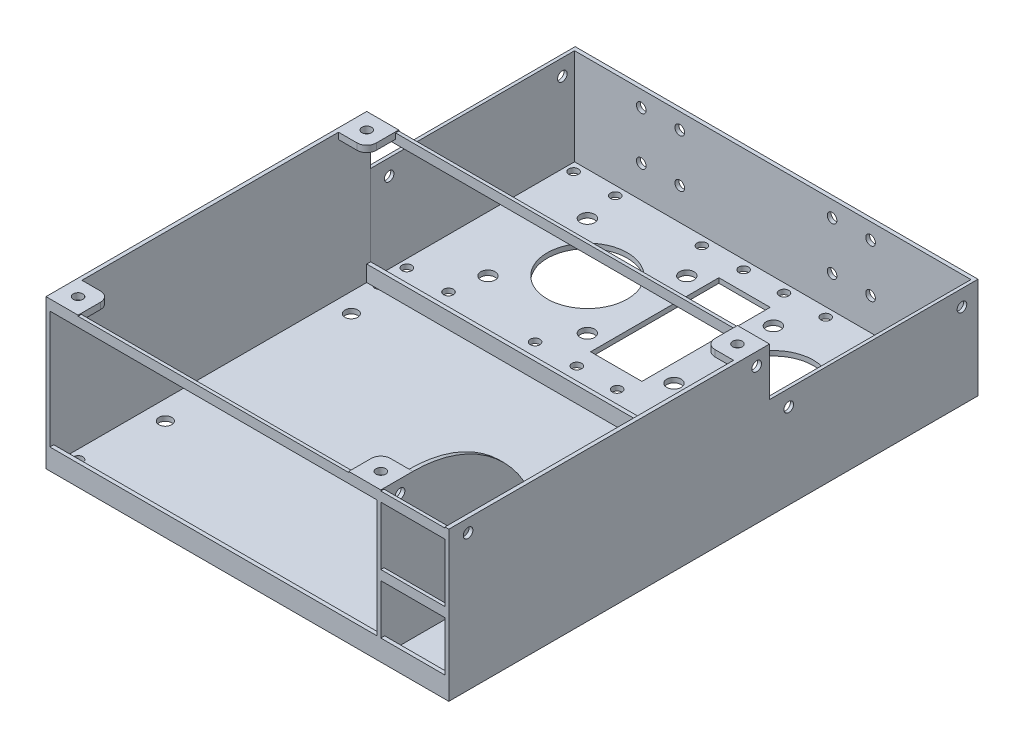
SolidWorks part; units mm, degrees
ref_plane "前视基准面" through (0, 0, 0) normal (0, 0, 1) x (1, 0, 0)
ref_plane "上视基准面" through (0, 0, 0) normal (0, 1, 0) x (1, 0, 0)
ref_plane "右视基准面" through (0, 0, 0) normal (1, 0, 0) x (0, 0, -1)
sketch "草图1" plane through (0, 0, 0) normal (0, 1, 0) x (1, 0, 0)
  line L0 (50.2, 20) -> (50.2, 102.702) construction
  line L1 (0, 0) -> (125.6, 0)
  line L2 (0, 0) -> (0, 165)
  line L3 (0, 165) -> (125.6, 165)
  line L4 (125.6, 0) -> (125.6, 165)
  line L5 (93.2, 0) -> (93.2, 165) construction
  line L6 (62.8, 0) -> (62.8, 178.9026) construction
  line L7 (109.4, 78) -> (119.4, 78)
  line L8 (109.4, 78) -> (109.4, 55)
  line L9 (109.4, 55) -> (119.4, 55)
  line L10 (119.4, 78) -> (119.4, 55)
  line L11 (33.8, 113.4656) -> (33.8, 152.8908) construction
  line L12 (14.2, 135) -> (54.4741, 135) construction
  line L13 (54.8, 155) -> (70.8, 155)
  line L14 (70.8, 155) -> (70.8, 115)
  line L15 (70.8, 115) -> (54.8, 115)
  line L16 (54.8, 155) -> (54.8, 115)
  line L17 (115.6, 172.6797) -> (115.6, 101.1747) construction
  line L18 (91.8, 135) -> (145.6116, 135) construction
  line L19 (95.6, 167.7897) -> (95.6, 105.1259) construction
  line L20 (4, 100) -> (4, -10.7198) construction
  circle A0 centre (93.2, 30) radius 2
  circle A1 centre (93.2, 88) radius 2
  circle A2 centre (7.2, 30) radius 2
  circle A3 centre (7.2, 88) radius 2
  circle A4 centre (33.8, 135) radius 12.5
  circle A5 centre (91.8, 135) radius 12.5
  circle A6 centre (49.3, 150.5) radius 2.25
  circle A7 centre (18.3, 150.5) radius 2.25
  circle A8 centre (49.3, 119.5) radius 2.25
  circle A9 centre (18.3, 119.5) radius 2.25
  circle A10 centre (107.3, 119.5) radius 2.25
  circle A11 centre (76.3, 119.5) radius 2.25
  circle A12 centre (107.3, 150.5) radius 2.25
  circle A13 centre (76.3, 150.5) radius 2.25
  circle A14 centre (122.1, 161) radius 1.5
  circle A15 centre (122.1, 109) radius 1.5
  circle A16 centre (109.1, 109) radius 1.5
  circle A17 centre (109.1, 161) radius 1.5
  circle A26 centre (16.5, 109) radius 1.5
  circle A27 centre (3.5, 109) radius 1.5
  circle A28 centre (16.5, 161) radius 1.5
  circle A29 centre (3.5, 161) radius 1.5
  circle A30 centre (69.1, 109) radius 1.5
  circle A31 centre (82.1, 109) radius 1.5
  circle A32 centre (82.1, 161) radius 1.5
  circle A33 centre (69.1, 161) radius 1.5
  circle A34 centre (56.5, 161) radius 1.5
  circle A35 centre (43.5, 161) radius 1.5
  circle A36 centre (56.5, 109) radius 1.5
  circle A37 centre (43.5, 109) radius 1.5
  circle A38 centre (4, 100) radius 1.5
  circle A39 centre (4, 6) radius 1.5
  circle A40 centre (121.6, 6) radius 1.5
  circle A41 centre (121.6, 100) radius 1.5
  point P52 (62.8, 115)
  point P53 (62.8, 155)
  dimension "D2" = 58
  dimension "D3" = 30
  dimension "D4" = 4
  dimension "D5" = 4
  dimension "D7" = 7.2
  dimension "D14" = 25
  dimension "D15" = 4.5
  dimension "D22" = 3
  dimension "D23" = 52
  dimension "D24" = 13
  dimension "D27" = 3
  dimension "D28" = 3
  dimension "D29" = 94
  dimension "D30" = 6
  dimension "D31" = 4
  dimension "D1" = 125.6
  dimension "D6" = 86
  dimension "D8" = 55
  dimension "D9" = 10
  dimension "D10" = 23
  dimension "D11" = 6.2
  dimension "D12" = 165
  dimension "D13" = 58
  dimension "D16" = 15.5
  dimension "D17" = 15.5
  dimension "D18" = 135
  dimension "D19" = 16
  dimension "D20" = 10
  dimension "D21" = 40
  dimension "D25" = 10
  dimension "D26" = 30
extrude "凸台-拉伸1" add sketch "草图1" along normal blind 1.5
sketch "草图2" plane through (0, 1.5, 0) normal (0, 1, 0) x (1, 0, 0)
  line L0 (125.6, 0) -> (125.6, 165) construction
  line L1 (0, 100) -> (1.2, 100)
  line L2 (0, 100) -> (0, 0)
  line L3 (0, 0) -> (1.2, 0)
  line L4 (1.2, 100) -> (1.2, 0)
  line L5 (0, 0) -> (125.6, 0) construction
  line L7 (103.2, 50) -> (104.4, 50)
  line L8 (103.2, 50) -> (103.2, 0)
  line L9 (103.2, 0) -> (104.4, 0)
  line L10 (104.4, 50) -> (104.4, 0)
  line L11 (125.6, 100) -> (124.4, 100)
  line L12 (125.6, 100) -> (125.6, 0)
  line L13 (125.6, 0) -> (124.4, 0)
  line L14 (124.4, 100) -> (124.4, 0)
  circle A0 centre (7.2, 88) radius 2 construction
  dimension "D4" = 6
  dimension "D5" = 1.2
  dimension "D1" = 102
  dimension "D2" = 1.2
  dimension "D3" = 1.2
  dimension "D6" = 50
  dimension "D7" = 100
  dimension "D8" = 100
extrude "凸台-拉伸2" add sketch "草图2" along normal blind 45
sketch "草图3" plane through (0, 1.5, 0) normal (0, 1, 0) x (1, 0, 0)
  line L0 (125.6, 0) -> (125.6, 100) construction
  line L1 (0, 0) -> (125.6, 0)
  line L2 (0, 0) -> (0, 1.2)
  line L3 (0, 1.2) -> (125.6, 1.2)
  line L4 (125.6, 0) -> (125.6, 1.2)
  line L5 (103.2, 50) -> (103.2, 0) construction
  line L6 (0, 100) -> (125.6, 100)
  line L8 (0, 98.8) -> (125.6, 98.8)
  line L10 (125.6, 47.2) -> (103.2, 47.2)
  line L11 (125.6, 47.2) -> (125.6, 48.4)
  line L12 (125.6, 48.4) -> (103.2, 48.4)
  line L13 (103.2, 47.2) -> (103.2, 48.4)
  line L14 (1.2, 100) -> (0, 100) construction
  line L16 (125.6, 165) -> (0, 165) construction
  line L18 (125.6, 100) -> (125.6, 98.8)
  line L19 (62.8, 165) -> (62.8, -17.6254) construction
  line L20 (0, 100) -> (0, 98.8)
  line L24 (125.6, 100) -> (125.6, 165) construction
  dimension "D1" = 1.2
  dimension "D2" = 1.2
  dimension "D3" = 1.2
  dimension "D4" = 46
extrude "凸台-拉伸3" add sketch "草图3" along normal blind 5
sketch "草图4" plane through (0, 0, 0) normal (0, 0, 1) x (1, 0, 0)
  line L0 (103.2, 46.5) -> (103.2, 6.5) construction
  line L1 (103.2, 25) -> (125.6, 25)
  line L2 (103.2, 25) -> (103.2, 22)
  line L3 (103.2, 22) -> (125.6, 22)
  line L4 (125.6, 25) -> (125.6, 22)
  line L5 (125.6, 46.5) -> (125.6, 0) construction
  line L6 (0, 0) -> (125.6, 0) construction
  line L7 (0, 46.5) -> (0, 0) construction
  line L8 (0, 46.2) -> (125.6, 46.2)
  line L9 (0, 46.2) -> (0, 43.2)
  line L10 (0, 43.2) -> (125.6, 43.2)
  line L11 (125.6, 46.2) -> (125.6, 43.2)
  dimension "D1" = 22
  dimension "D2" = 3
  dimension "D3" = 43.2
  dimension "D4" = 3
extrude "凸台-拉伸4" add sketch "草图4" against normal blind 1
sketch "草图5" plane through (0, 0, -100) normal (0, 0, -1) x (-1, 0, 0)
  line L0 (0, 1.5) -> (0, 0) construction
  line L1 (-125.6, 46.2) -> (0, 46.2)
  line L2 (-125.6, 46.2) -> (-125.6, 43.2)
  line L3 (-125.6, 43.2) -> (0, 43.2)
  line L4 (0, 46.2) -> (0, 43.2)
  line L5 (-1.2, 43.2) -> (-103.2, 43.2) construction
  line L6 (-125.6, 46.5) -> (-125.6, 1.5) construction
extrude "凸台-拉伸5" add sketch "草图5" against normal blind 1
fillet "圆角1" radius 40 1 edges at (103.8, 46.5, -50)
sketch "草图6" plane through (0, 46.5, 0) normal (0, 1, 0) x (1, 0, 0)
  line L0 (124.35, 100) -> (124.35, -10.7298) construction
  line L1 (0, 0) -> (10, 0)
  line L2 (0, 0) -> (0, 10)
  line L3 (0, 10) -> (7, 10)
  line L4 (10, 0) -> (10, 7)
  line L5 (125.6, 100) -> (123.1, 100) construction
  line L6 (0, 50) -> (151.8098, 50) construction
  line L7 (0, 100) -> (0, 0) construction
  line L16 (10, 100) -> (10, 93)
  line L17 (0, 90) -> (7, 90)
  line L18 (0, 100) -> (0, 90)
  line L19 (0, 100) -> (10, 100)
  line L24 (52.2, 0) -> (52.2, 16.9904) construction
  line L25 (103.2, 0) -> (1.2, 0) construction
  line L26 (94.4, 0) -> (94.4, 7)
  line L27 (104.4, 10) -> (97.4, 10)
  line L28 (104.4, 0) -> (104.4, 10)
  line L29 (104.4, 0) -> (94.4, 0)
  line L30 (62.8, 99) -> (62.8, 68.0456) construction
  line L31 (1.2, 99) -> (124.4, 99) construction
  line L32 (125.6, 100) -> (115.6, 100)
  line L33 (125.6, 100) -> (125.6, 90)
  line L34 (125.6, 90) -> (118.6, 90)
  line L35 (115.6, 100) -> (115.6, 93)
  circle A0 centre (5, 5) radius 1.5
  arc A1 (7, 10) -> (10, 7) centre (7, 7) cw
  arc A6 (7, 90) -> (10, 93) centre (7, 93) ccw
  circle A7 centre (5, 95) radius 1.5
  arc A10 (97.4, 10) -> (94.4, 7) centre (97.4, 7) ccw
  circle A11 centre (99.4, 5) radius 1.5
  circle A12 centre (120.6, 95) radius 1.5
  arc A13 (118.6, 90) -> (115.6, 93) centre (118.6, 93) cw
  point P17 (10, 10)
  point P30 (115.6, 90)
  point P44 (10, 90)
  point P57 (94.4, 10)
  dimension "D1" = 3
  dimension "D2" = 5
  dimension "D6" = 3
  dimension "D3" = 5
  dimension "D4" = 10
  dimension "D5" = 10
extrude "凸台-拉伸6" add sketch "草图6" against normal blind 2
sketch "草图8" plane through (0, 1.5, 0) normal (0, 1, 0) x (1, 0, 0)
  line L0 (125.6, 165) -> (0, 165) construction
  line L1 (125.6, 100) -> (124.6, 100)
  line L2 (125.6, 100) -> (125.6, 165)
  line L4 (124.6, 100) -> (124.6, 163.8)
  line L5 (124.6, 163.8) -> (1, 163.8)
  line L6 (0, 100) -> (1, 100)
  line L7 (0, 100) -> (0, 165)
  line L8 (0, 165) -> (125.6, 165)
  line L9 (1, 100) -> (1, 163.8)
  dimension "D1" = 1
  dimension "D2" = 1.2
  dimension "D3" = 1
extrude "凸台-拉伸7" add sketch "草图8" along normal blind 30
sketch "草图9" plane through (0, 0, -165) normal (0, 0, -1) x (-1, 0, 0)
  line L0 (-62.8, 0) -> (-62.8, 59.3755) construction
  line L1 (-125.6, 0) -> (0, 0) construction
  line L2 (-33.8, 26.5) -> (-21.8, 26.5) construction
  line L3 (-33.8, 26.5) -> (-33.8, 11.5) construction
  line L4 (-33.8, 11.5) -> (-21.8, 11.5) construction
  line L5 (-21.8, 11.5) -> (-21.8, 26.5) construction
  line L6 (-125.6, 31.5) -> (0, 31.5) construction
  line L7 (-57.55, -4.3984) -> (-57.55, 38.5088) construction
  line L8 (-93.3, 11.5) -> (-93.3, 26.5) construction
  line L9 (-81.3, 11.5) -> (-93.3, 11.5) construction
  line L10 (-81.3, 26.5) -> (-81.3, 11.5) construction
  line L11 (-81.3, 26.5) -> (-93.3, 26.5) construction
  circle A0 centre (-33.8, 26.5) radius 1.5
  circle A1 centre (-21.8, 26.5) radius 1.5
  circle A2 centre (-21.8, 11.5) radius 1.5
  circle A3 centre (-33.8, 11.5) radius 1.5
  circle A4 centre (-81.3, 11.5) radius 1.5
  circle A5 centre (-93.3, 11.5) radius 1.5
  circle A6 centre (-93.3, 26.5) radius 1.5
  circle A7 centre (-81.3, 26.5) radius 1.5
  dimension "D1" = 3
  dimension "D2" = 3
  dimension "D3" = 3
  dimension "D4" = 3
  dimension "D7" = 15
  dimension "D8" = 12
  dimension "D9" = 47.5
  dimension "D5" = 29
  dimension "D6" = 5
extrude "切除-拉伸1" cut sketch "草图9" against normal up to next
sketch "草图10" plane through (125.6, 0, 0) normal (1, 0, 0) x (0, 0, -1)
  line L0 (119.8489, 42.5) -> (-1.2798, 42.5) construction
  line L1 (0, 46.5) -> (100, 46.5) construction
  line L2 (100, 46.5) -> (100, 31.5) construction
  circle A0 centre (96, 42.5) radius 1.5
  circle A1 centre (6, 42.5) radius 1.5
  dimension "D1" = 3
  dimension "D2" = 3
  dimension "D3" = 90
  dimension "D4" = 4
  dimension "D5" = 4
extrude "切除-拉伸2" cut sketch "草图10" against normal through all
sketch "草图11" plane through (125.6, 0, 0) normal (1, 0, 0) x (0, 0, -1)
  line L0 (160, 26.5) -> (82.9025, 26.5) construction
  line L1 (165, 31.5) -> (165, 0) construction
  line L2 (100, 31.5) -> (165, 31.5) construction
  circle A0 centre (160, 26.5) radius 1.5
  circle A1 centre (106, 26.5) radius 1.5
  dimension "D1" = 3
  dimension "D2" = 3
  dimension "D3" = 5
  dimension "D4" = 5
  dimension "D5" = 54
extrude "切除-拉伸3" cut sketch "草图11" against normal through all
